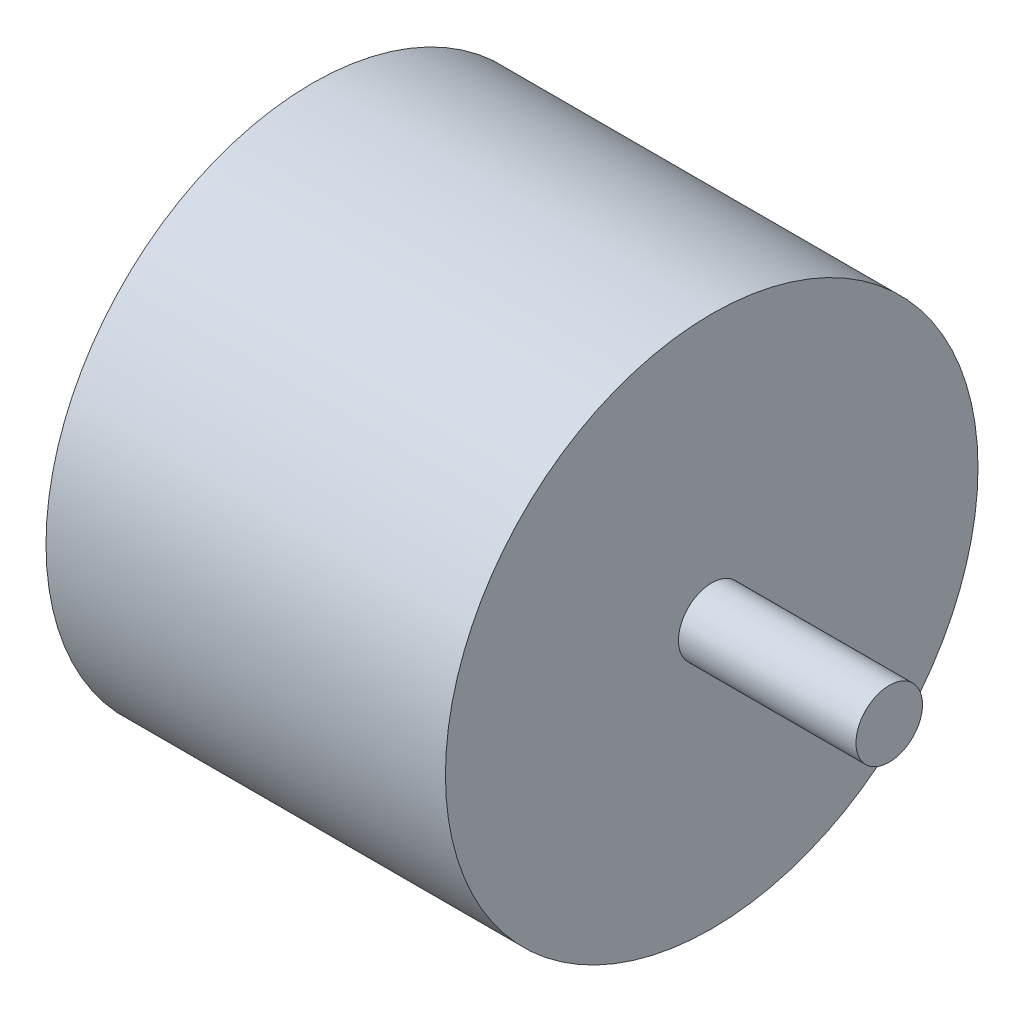
SolidWorks part; units mm, degrees
ref_plane "前视基准面" through (0, 0, 0) normal (0, 0, 1) x (1, 0, 0)
ref_plane "上视基准面" through (0, 0, 0) normal (0, 1, 0) x (1, 0, 0)
ref_plane "右视基准面" through (0, 0, 0) normal (1, 0, 0) x (0, 0, -1)
sketch "草图1" plane through (0, 0, 0) normal (1, 0, 0) x (0, 0, -1)
  circle A0 centre (0, 0) radius 12
extrude "凸台-拉伸1" add sketch "草图1" along normal blind 18
sketch "草图2" plane through (18, 0, 0) normal (1, 0, 0) x (0, 0, -1)
  circle A0 centre (0, 0) radius 1.5
extrude "凸台-拉伸2" add sketch "草图2" along normal blind 8
